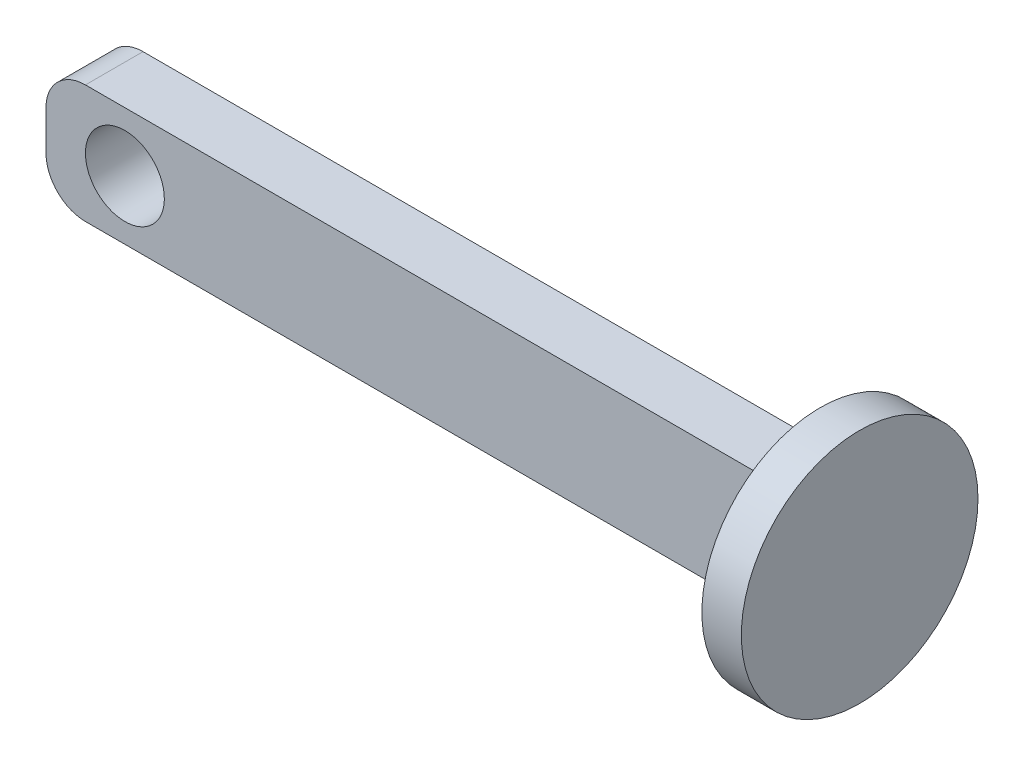
SolidWorks part; units mm, degrees
ref_plane "Front Plane" through (0, 0, 0) normal (0, 0, 1) x (1, 0, 0)
ref_plane "Top Plane" through (0, 0, 0) normal (0, 1, 0) x (1, 0, 0)
ref_plane "Right Plane" through (0, 0, 0) normal (1, 0, 0) x (0, 0, -1)
sketch "Sketch1" plane through (0, 0, 0) normal (1, 0, 0) x (0, 0, -1)
  line L0 (-2.3177, 4.7625) -> (2.3178, -4.7625) construction
  line L1 (-2.3177, 4.7625) -> (2.3177, 4.7625)
  line L2 (-2.3177, 4.7625) -> (-2.3177, -4.7625)
  line L3 (-2.3177, -4.7625) -> (2.3178, -4.7625)
  line L4 (2.3177, 4.7625) -> (2.3178, -4.7625)
  circle A0 centre (0, 0) radius 9.525
  dimension "D1" = 19.05
  dimension "D2" = 4.6355
  dimension "D3" = 9.525
extrude "Boss-Extrude1" add sketch "Sketch1" along normal blind 3.175 contours A0
sketch "Sketch2" plane through (0, 0, 0) normal (-1, 0, 0) x (0, 0, 1)
  line L0 (2.3177, 4.7625) -> (2.3177, -4.7625) construction
  line L1 (2.3177, -4.7625) -> (-2.3178, -4.7625) construction
  line L2 (-2.3177, 4.7625) -> (-2.3178, -4.7625) construction
  line L3 (2.3177, 4.7625) -> (-2.3177, 4.7625) construction
  line L4 (2.3177, 4.7625) -> (2.3177, -4.7625)
  line L5 (2.3177, -4.7625) -> (-2.3178, -4.7625)
  line L6 (-2.3177, 4.7625) -> (-2.3178, -4.7625)
  line L7 (2.3177, 4.7625) -> (-2.3177, 4.7625)
extrude "Boss-Extrude2" add sketch "Sketch2" along normal blind 60
fillet "Fillet1" radius 3.175 2 edges at (-60, -4.7625, 0) (-60, 4.7625, 0)
sketch "Sketch3" plane through (0, 0, -2.3178) normal (0, 0, -1) x (-1, 0, 0)
  line L0 (60, 0) -> (53.65, 0) construction
  line L1 (60, 1.5875) -> (60, -1.5875) construction
  circle A0 centre (53.65, 0) radius 3.175
  dimension "D1" = 6.35
  dimension "D2" = 6.35
extrude "Cut-Extrude1" cut sketch "Sketch3" against normal through all
